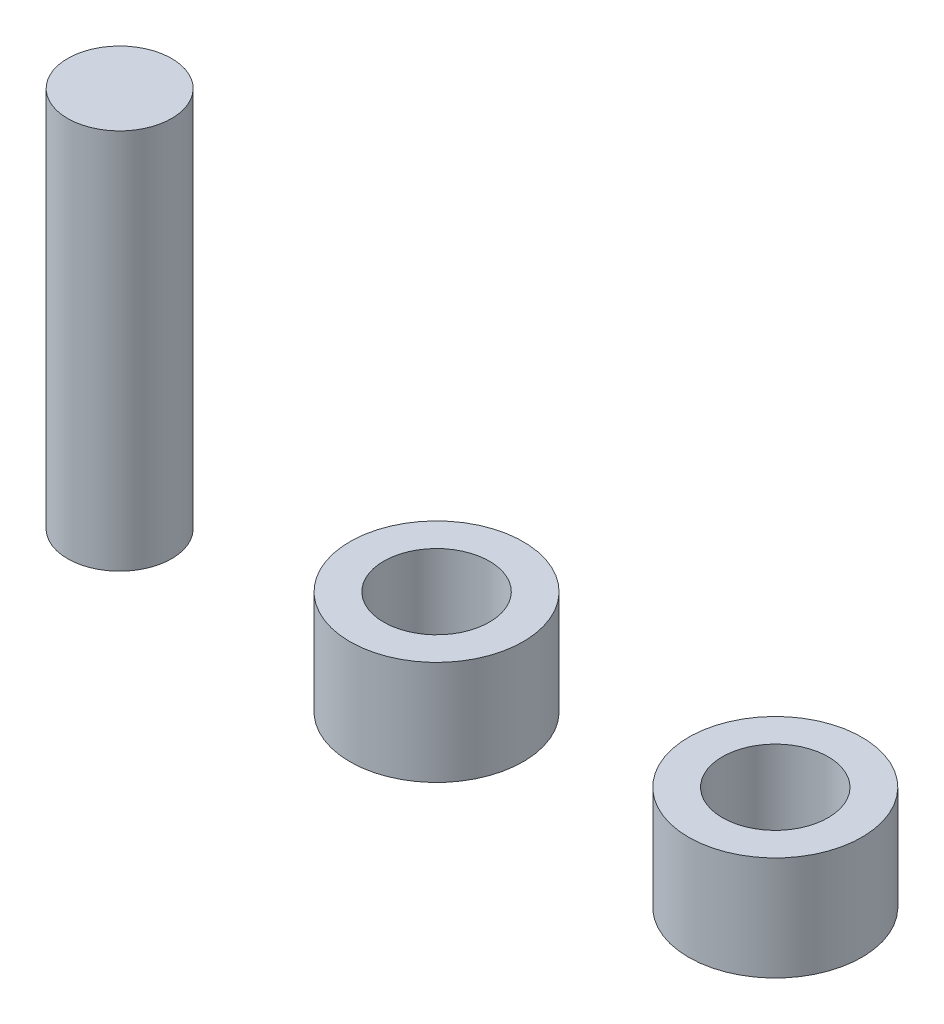
SolidWorks part; units mm, degrees
ref_plane "Front Plane" through (0, 0, 0) normal (0, 0, 1) x (1, 0, 0)
ref_plane "Top Plane" through (0, 0, 0) normal (0, 1, 0) x (1, 0, 0)
ref_plane "Right Plane" through (0, 0, 0) normal (1, 0, 0) x (0, 0, -1)
sketch "Sketch1" plane through (0, 0, 0) normal (0, 1, 0) x (1, 0, 0)
  line L0 (-9.6635, 0) -> (10.2555, 0) construction
  circle A0 centre (0.1146, 0) radius 2.5
  circle A1 centre (0.1146, 0) radius 1.525
  dimension "D1" = 5
  dimension "D2" = 3.05
extrude "Boss-Extrude1" add sketch "Sketch1" along normal blind 3
sketch "Sketch2" plane through (0, 0, 0) normal (0, 1, 0) x (1, 0, 0)
  line L0 (-13.1071, 0) -> (16.2343, 0) construction
  circle A0 centre (-9.0273, 0) radius 1.5
  dimension "D1" = 3
extrude "Boss-Extrude2" add sketch "Sketch2" along normal blind 11 separate body contours A0
ref_plane "Plane1" through (5, 0, 0) normal (1, 0, 0) x (0, 0, -1)
mirror "Mirror1" about plane through (5, 0, 0) normal (1, 0, 0) of bodies 101
